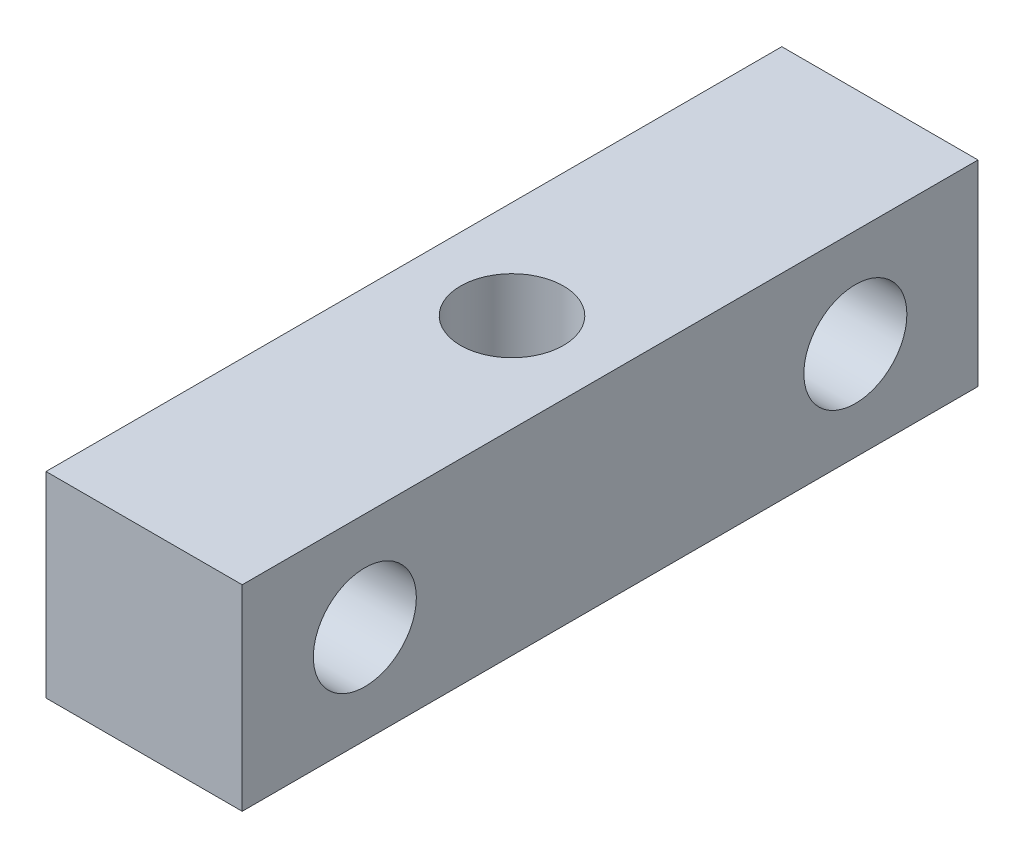
SolidWorks part; units mm, degrees
material "玻纤增强尼龙1010"
ref_plane "前视基准面" through (0, 0, 0) normal (0, 0, 1) x (1, 0, 0)
ref_plane "上视基准面" through (0, 0, 0) normal (0, 1, 0) x (1, 0, 0)
ref_plane "右视基准面" through (0, 0, 0) normal (1, 0, 0) x (0, 0, -1)
sketch "草图2" plane through (0, 0, 0) normal (0, 0, 1) x (1, 0, 0)
  line L1 (-4, -4) -> (4, -4)
  line L2 (-4, -4) -> (-4, 4)
  line L3 (-4, 4) -> (4, 4)
  line L4 (4, -4) -> (4, 4)
  line L5 (-4, -4) -> (4, 4) construction
  line L6 (-4, 4) -> (4, -4) construction
  point P0 (0, 0)
  dimension "D1" = 8
  dimension "D2" = 8
extrude "凸台-拉伸1" add sketch "草图2" along normal blind 30
sketch "草图3" plane through (0, 4, 0) normal (0, 1, 0) x (1, 0, 0)
  line L0 (0, 0) -> (0, -30) construction
  line L1 (4, -30) -> (-4, -30) construction
  circle A0 centre (0, -15) radius 2.1
  dimension "D1" = 4.2
extrude "切除-拉伸1" cut sketch "草图3" against normal through all
sketch "草图4" plane through (4, 0, 0) normal (1, 0, 0) x (0, 0, -1)
  line L0 (0, 0) -> (-30, 0) construction
  line L1 (-30, -4) -> (-30, 4) construction
  circle A0 centre (-25, 0) radius 2.1
  circle A1 centre (-5, 0) radius 2.1
  dimension "D1" = 4.2
  dimension "D2" = 5
  dimension "D3" = 5
extrude "切除-拉伸2" cut sketch "草图4" against normal through all
